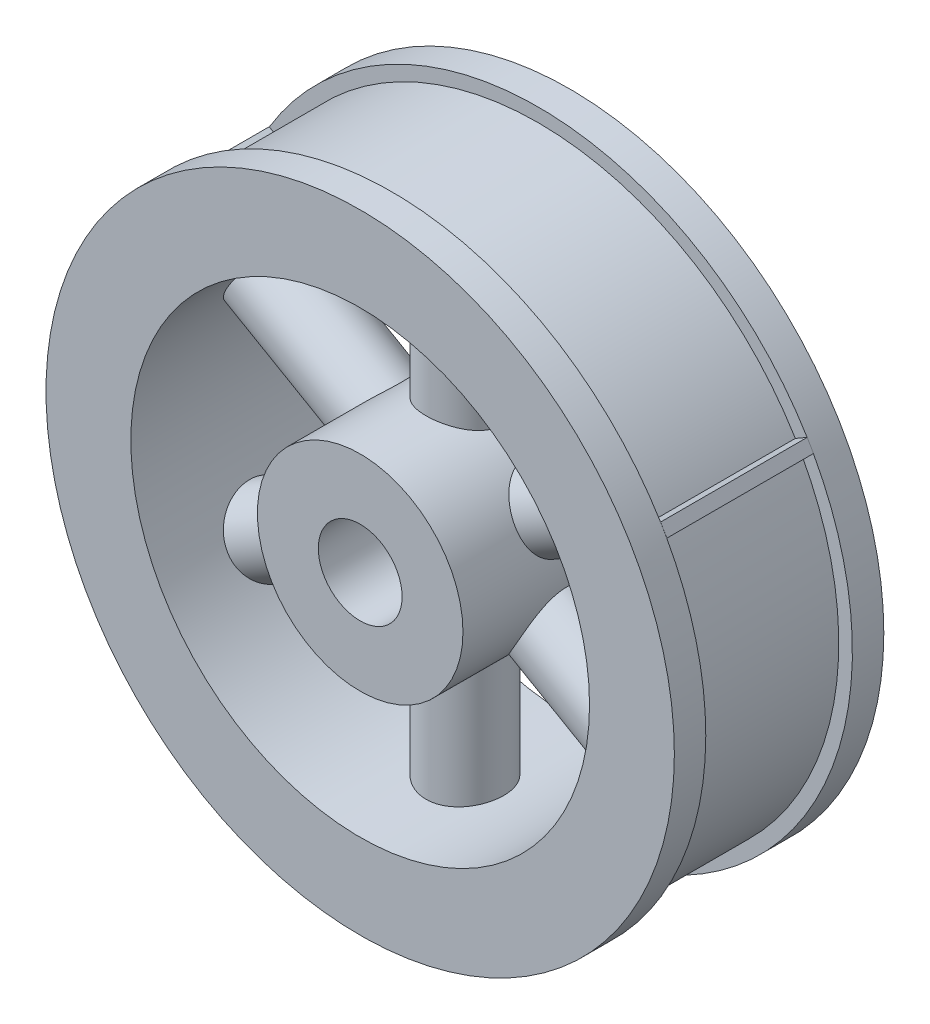
SolidWorks part; units mm, degrees
other "Markup1"
sketch "Sketch9" plane through (15, 15, 0) normal (0.4109, 0.6751, -0.6127) x (0.4132, 0.4611, 0.7853)
material "ABS"
ref_plane "Front Plane" through (0, 0, 0) normal (0, 0, 1) x (1, 0, 0)
ref_plane "Top Plane" through (0, 0, 0) normal (0, 1, 0) x (1, 0, 0)
ref_plane "Right Plane" through (0, 0, 0) normal (1, 0, 0) x (0, 0, -1)
sketch "Sketch2" plane through (0, 0, 0) normal (0, 0, 1) x (1, 0, 0)
  line L1 (2, 0) -> (-2, 0) construction
  circle A0 centre (0, 0) radius 2
  circle A1 centre (0, 0) radius 15
  circle A2 centre (0, 0) radius 4.9074
  circle A3 centre (0, 0) radius 14.35
extrude "Boss-Extrude1" add sketch "Sketch2" along normal blind 10
sketch "Sketch3" plane through (0, 0, 0) normal (0, 0, 1) x (1, 0, 0)
  circle A0 centre (0, 0) radius 14.35
  circle A1 centre (0, 0) radius 15
  circle A2 centre (0, 0) radius 2
  circle A3 centre (0, 0) radius 10.9501
extrude "Boss-Extrude2" add sketch "Sketch3" along normal blind 10 separate body contours A0 A3
sketch "Sketch4" plane through (0, 0, 0) normal (0, 0, 1) x (1, 0, 0)
  circle A0 centre (0, 0) radius 14.35
  circle A1 centre (0, 0) radius 15
extrude "Boss-Extrude3" add sketch "Sketch4" along normal blind 1.5
sketch "Sketch5" plane through (0, 0, 10) normal (0, 0, 1) x (1, 0, 0)
  circle A0 centre (0, 0) radius 14.35
  circle A1 centre (0, 0) radius 15
extrude "Boss-Extrude4" add sketch "Sketch5" against normal blind 1.5
ref_plane "Plane1" through (0, 0, 0) normal (0, 1, 0) x (-1, 0, 0)
sketch "Sketch7" plane through (0, 0, 0) normal (0, 1, 0) x (-1, 0, 0)
  line L0 (0, 0) -> (0, 10)
  line L1 (15, 10) -> (-15, 10) construction
  circle A0 centre (0, 5) radius 1.8546
extrude "Boss-Extrude5" add sketch "Sketch7" against normal blind 12.5 contours L0 A0 | L0 A0
pattern_circular "CirPattern1" count 6 over 360 about axis through (0, 0, 10) along (0, 0, 1) of "Boss-Extrude5"
ref_plane "Plane2" through (0, 0, 1.5) normal (0, 0, 1) x (1, 0, 0)
sketch "Sketch8" plane through (0, 0, 1.5) normal (0, 0, 1) x (1, 0, 0)
  line L0 (0, -14.35) -> (0, -15)
  line L2 (-0.299, -15.0031) -> (0.299, -15.0031)
  line L3 (-0.299, -15.0031) -> (-0.299, -14.3469)
  line L4 (-0.299, -14.3469) -> (0.299, -14.3469)
  line L5 (0.299, -15.0031) -> (0.299, -14.3469)
  line L6 (-0.299, -15.0031) -> (0.299, -14.3469) construction
  line L7 (-0.299, -14.3469) -> (0.299, -15.0031) construction
  circle A0 centre (0, 0) radius 14.35 construction
  circle A3 centre (0, 0) radius 15 construction
  point P2 (0, -14.675)
  point P6 (0, -14.35)
extrude "Boss-Extrude6" add sketch "Sketch8" along normal up to surface (7 mm away) up to face at (14.35, 0, 8.5)
pattern_circular "CirPattern2" count 3 over 360 about axis through (0, 0, 0) along (0, 0, 1) of "Boss-Extrude6"
ref_plane "Plane3" through (0, 0, 0) normal (0, 0, -1) x (-1, 0, 0)
sketch "Sketch10" plane through (0, 0, 0) normal (0, 0, -1) x (-1, 0, 0)
  circle A0 centre (0, 0) radius 2
extrude "Cut-Extrude1" cut sketch "Sketch10" against normal up to surface (10 mm away) up to face at (4.9074, 0, 10)
